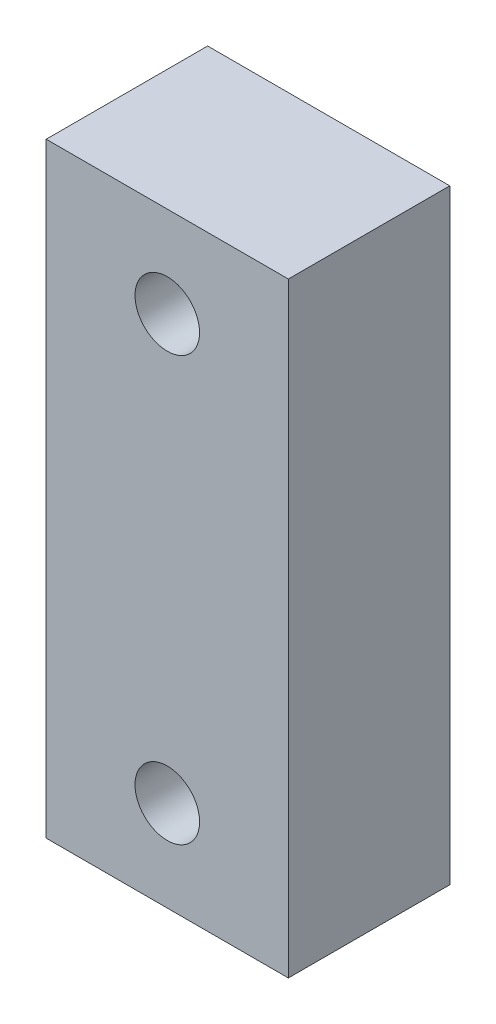
SolidWorks part; units mm, degrees
ref_plane "前视基准面" through (0, 0, 0) normal (0, 0, 1) x (1, 0, 0)
ref_plane "上视基准面" through (0, 0, 0) normal (0, 1, 0) x (1, 0, 0)
ref_plane "右视基准面" through (0, 0, 0) normal (1, 0, 0) x (0, 0, -1)
sketch "草图1" plane through (0, 0, 0) normal (0, 0, 1) x (1, 0, 0)
  line L1 (-15, -37.5) -> (15, -37.5)
  line L2 (-15, -37.5) -> (-15, 37.5)
  line L3 (-15, 37.5) -> (15, 37.5)
  line L4 (15, -37.5) -> (15, 37.5)
  line L5 (-15, -37.5) -> (15, 37.5) construction
  line L6 (-15, 37.5) -> (15, -37.5) construction
  circle A0 centre (0, 26.25) radius 4
  circle A1 centre (0, -26.25) radius 4
  point P0 (0, 0)
extrude "凸台-拉伸1" add sketch "草图1" along normal blind 20
